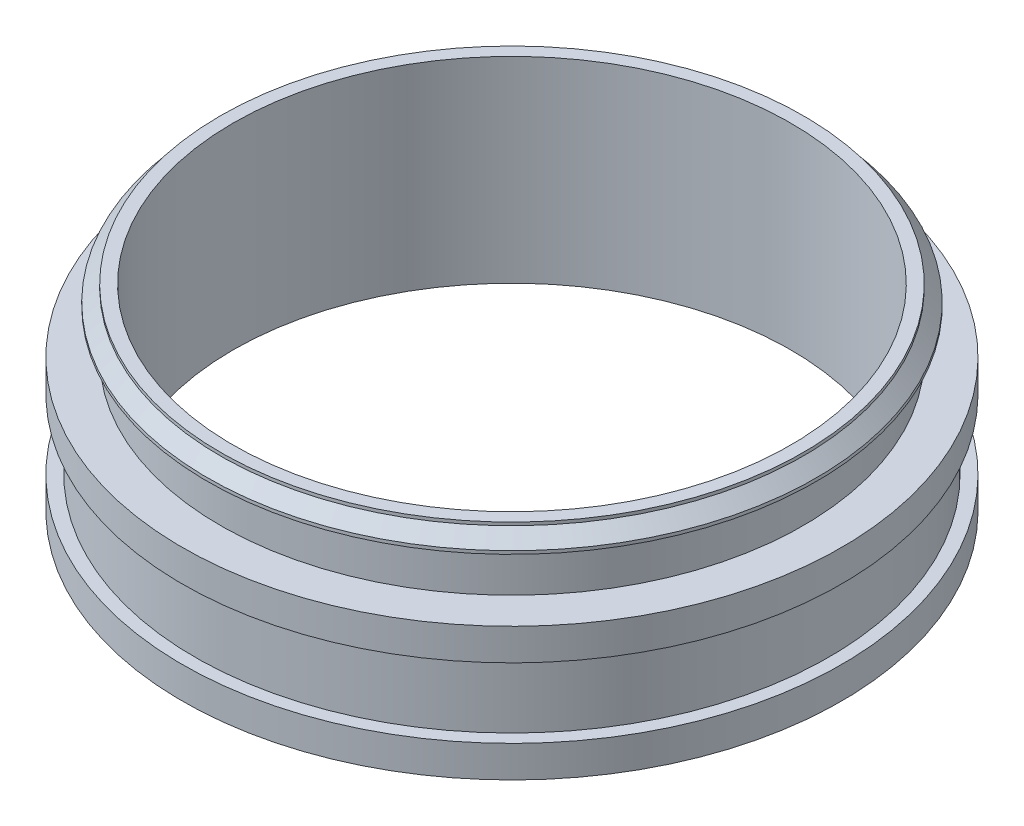
SolidWorks part; units mm, degrees
ref_plane "Front Plane" through (0, 0, 0) normal (0, 0, 1) x (1, 0, 0)
ref_plane "Top Plane" through (0, 0, 0) normal (0, 1, 0) x (1, 0, 0)
ref_plane "Right Plane" through (0, 0, 0) normal (1, 0, 0) x (0, 0, -1)
ref_plane "Plane1" through (0, 0, 0) normal (0, 0, -1) x (-1, 0, 0)
sketch "Sketch1" plane through (0, 0, 0) normal (0, 0, -1) x (-1, 0, 0)
  line L0 (-46, 11.3812) -> (-46, 4.3812)
  line L1 (-46, 4.3812) -> (-52, 4.3812)
  line L2 (-52, 4.3812) -> (-52, -0.6188)
  line L3 (-52, -0.6188) -> (-50, -0.6188)
  line L4 (-50, -0.6188) -> (-50, -11.6188)
  line L5 (-50, -11.6188) -> (-52, -11.6188)
  line L6 (-52, -11.6188) -> (-52, -16.6188)
  line L7 (-52, -16.6188) -> (-44, -16.6188)
  line L8 (-44, -16.6188) -> (-44, 14.3812)
  line L9 (-44, 14.3812) -> (-46, 14.3812)
  line L10 (-46, 14.3812) -> (-46, 13.8812)
  line L11 (-46, 13.8812) -> (-48, 11.8812)
  line L12 (-48, 11.8812) -> (-48, 11.3812)
  line L13 (-48, 11.3812) -> (-46, 11.3812)
  line L14 (0, -16.6188) -> (0, 14.3812) construction
revolve "Revolve1" add sketch "Sketch1" angle 360 about L14
